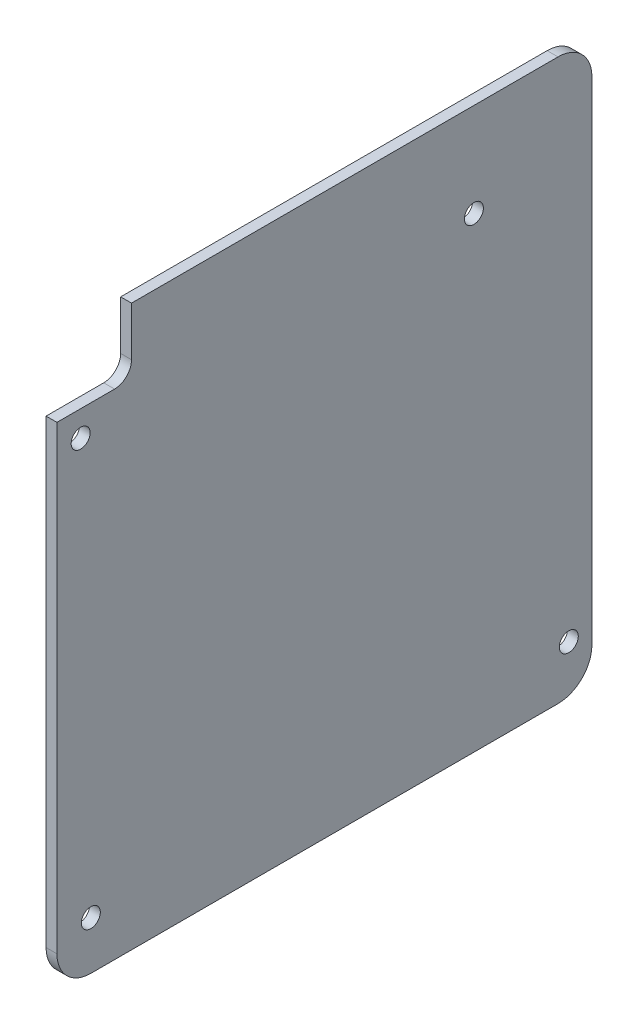
SolidWorks part; units mm, degrees
ref_plane "Front Plane" through (0, 0, 0) normal (0, 0, 1) x (1, 0, 0)
ref_plane "Top Plane" through (0, 0, 0) normal (0, 1, 0) x (1, 0, 0)
ref_plane "Right Plane" through (0, 0, 0) normal (1, 0, 0) x (0, 0, -1)
sketch "Sketch1" plane through (0, 0, 0) normal (1, 0, 0) x (0, 0, -1)
  line L1 (-34.4685, -41.3233) -> (34.4401, -41.3233)
  line L2 (-39.4685, -36.3233) -> (-39.4685, 31.5635)
  line L3 (-28.4685, 41.2935) -> (34.4401, 41.2935)
  line L4 (39.4401, -36.3233) -> (39.4401, 36.2935)
  line L5 (-39.4685, -41.3233) -> (39.4401, 41.2935) construction
  line L6 (-30.1251, 31.5635) -> (39.4401, -41.3233) construction
  line L9 (-39.4685, 31.5635) -> (-30.9685, 31.5635)
  line L10 (-28.4685, 41.2935) -> (-28.4685, 34.0635)
  circle A0 centre (-35.9685, 27.7935) radius 1.4
  circle A1 centre (22.0315, 27.4935) radius 1.4
  circle A2 centre (-34.4685, -34.2065) radius 1.4
  circle A3 centre (36.0315, -34.2065) radius 1.4
  arc A4 (-30.9685, 31.5635) -> (-28.4685, 34.0635) centre (-30.9685, 34.0635) ccw
  arc A5 (-34.4685, -41.3233) -> (-39.4685, -36.3233) centre (-34.4685, -36.3233) cw
  arc A6 (34.4401, -41.3233) -> (39.4401, -36.3233) centre (34.4401, -36.3233) ccw
  arc A7 (34.4401, 41.2935) -> (39.4401, 36.2935) centre (34.4401, 36.2935) cw
  point P0 (0, 0)
  point P16 (-28.4685, 31.5635)
  point P29 (21.9702, 25.1275)
  point P30 (0, 0)
  point P31 (0, 0)
  dimension "D2" = 3.5
  dimension "D1" = 2.5
  dimension "D10" = 5
  dimension "D3" = 58
  dimension "D4" = 14
  dimension "D5" = 61.7
  dimension "D6" = 13.5
  dimension "D7" = 1.5
  dimension "D8" = 9.73
  dimension "D9" = 11
  dimension "D11" = 62
  dimension "D12" = 0.3
extrude "Boss-Extrude1" add sketch "Sketch1" along normal mid plane 1.6
